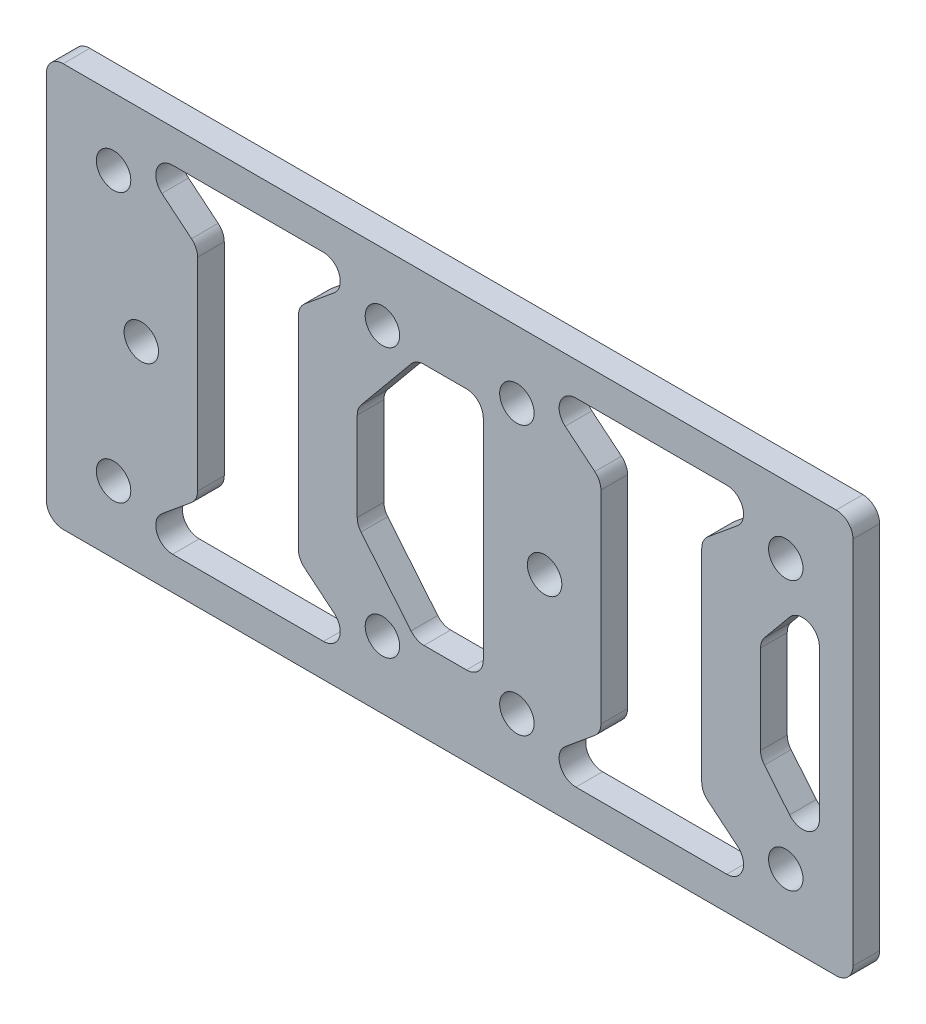
SolidWorks part; units mm, degrees
ref_plane "Front Plane" through (0, 0, 0) normal (0, 0, 1) x (1, 0, 0)
ref_plane "Top Plane" through (0, 0, 0) normal (0, 1, 0) x (1, 0, 0)
ref_plane "Right Plane" through (0, 0, 0) normal (1, 0, 0) x (0, 0, -1)
sketch "Sketch1" plane through (0, 0, 0) normal (0, 0, 1) x (1, 0, 0)
  line L0 (0, 0) -> (50000, 0) construction
  line L1 (48, -24) -> (-48, -24)
  line L2 (48, -24) -> (48, 24)
  line L3 (48, 24) -> (-48, 24)
  line L4 (-48, -24) -> (-48, 24)
  line L5 (48, -24) -> (-24, 12) construction
  line L6 (48, 24) -> (-48, -24) construction
  line L7 (0, 0) -> (0, -50000) construction
  line L8 (-38.5449, 20.05) -> (-30, 13)
  line L9 (-40, 16) -> (-8, 16) construction
  line L10 (-40, 16) -> (-40, -16) construction
  line L11 (-40, -16) -> (-8, -16) construction
  line L12 (-8, 16) -> (-8, -16) construction
  line L13 (-40, 16) -> (-8, -16) construction
  line L14 (-40, -16) -> (-8, 16) construction
  line L16 (-18, 13) -> (-9.4551, 20.05)
  line L17 (-9.4551, 20.05) -> (-38.5449, 20.05)
  line L18 (50, 26) -> (-50, 26) construction
  line L19 (-50, -26) -> (-50, 26) construction
  line L20 (50, -26) -> (-50, -26) construction
  line L21 (50, -26) -> (50, 26) construction
  line L22 (44, 20) -> (-44, 20) construction
  line L23 (-44, -20) -> (-44, 20) construction
  line L24 (44, -20) -> (-44, -20) construction
  line L25 (44, -20) -> (44, 20) construction
  line L26 (-18, -13) -> (-9.4551, -20.05)
  line L28 (-38.5449, -20.05) -> (-30, -13)
  line L29 (-9.4551, -20.05) -> (-38.5449, -20.05)
  line L30 (-44, 14.4843) -> (-44, -14.4843) construction
  line L31 (-44, -14.4843) -> (-37, -6) construction
  line L32 (-37, -6) -> (-37, 6) construction
  line L33 (-37, 6) -> (-44, 14.4843) construction
  line L34 (-24, 0) -> (-24, 50000) construction
  line L35 (-11, -6) -> (-11, 6)
  line L36 (-4, -14.4843) -> (-11, -6)
  line L38 (-11, 6) -> (-4, 14.4843)
  line L42 (11, -6) -> (11, -5.5)
  line L44 (38.5449, -20.05) -> (30, -13)
  line L45 (9.4551, -20.05) -> (38.5449, -20.05)
  line L46 (18, -13) -> (9.4551, -20.05)
  line L47 (37, -6) -> (37, 6)
  line L48 (44, -14.4843) -> (37, -6)
  line L49 (44, 14.4843) -> (44, -14.4843)
  line L50 (37, 6) -> (44, 14.4843)
  line L51 (18, 13) -> (9.4551, 20.05)
  line L53 (38.5449, 20.05) -> (30, 13)
  line L54 (9.4551, 20.05) -> (38.5449, 20.05)
  line L55 (-44, -14.4843) -> (-37, -6) construction
  line L56 (-44, 14.4843) -> (-44, -14.4843) construction
  line L57 (-37, 6) -> (-44, 14.4843) construction
  line L58 (-37, -6) -> (-37, 6) construction
  line L59 (-4, 14.4843) -> (4, 14.4843)
  line L60 (-4, -14.4843) -> (4, -14.4843)
  line L61 (4, 14.4843) -> (4, -14.4843)
  line L62 (18, 13) -> (18, -13)
  line L63 (30, 13) -> (30, -13)
  line L64 (-30, 13) -> (-30, -13)
  line L65 (-18, 13) -> (-18, -13)
  line L66 (-25.7605, 12.8802) -> (-48, 24) construction
  line L67 (11, 5.5) -> (11, 6)
  circle A0 centre (-40, 16) radius 2.05
  circle A1 centre (-8, 16) radius 2.05
  circle A2 centre (-8, -16) radius 2.05
  circle A3 centre (-40, -16) radius 2.05
  circle A4 centre (-24, 0) radius 11 construction
  circle A5 centre (-8, -16) radius 4.05 construction
  circle A6 centre (-40, -16) radius 4.05 construction
  arc A7 (-25.7605, 12.8802) -> (-24, 13) centre (-24, 0) ccw construction
  circle A8 centre (-40, 16) radius 4.05 construction
  circle A9 centre (-8, 16) radius 4.05 construction
  circle A10 centre (-8, -16) radius 0.05 construction
  circle A11 centre (-40, -16) radius 0.05 construction
  circle A12 centre (-24, 0) radius 9 construction
  circle A13 centre (-40, 16) radius 0.05 construction
  circle A14 centre (-8, 16) radius 0.05 construction
  circle A15 centre (8, 16) radius 2.05
  circle A16 centre (8, -16) radius 2.05
  circle A17 centre (40, -16) radius 2.05
  circle A18 centre (24, 0) radius 11 construction
  circle A19 centre (40, 16) radius 2.05
  circle A20 centre (-36.7, 0) radius 2.05
  circle A21 centre (11.3, 0) radius 2.05
  circle A22 centre (-24, 0) radius 13 construction
  point P0 (0, 0)
  point P10 (-24, 0)
  dimension "D5" = 4.1
  dimension "D6" = 22
  dimension "D1" = 96
  dimension "D2" = 48
  dimension "D3" = 32
  dimension "D4" = 8
  dimension "D11" = 12
  dimension "D12" = 12
  dimension "D13" = 48
  dimension "D14" = 11.3
  dimension "D7" = 2
  dimension "D8" = 2
  dimension "D9" = 2
  dimension "D10" = 4
extrude "Boss-Extrude1" add sketch "Sketch1" along normal blind 3.175
fillet "Fillet1" radius 2 30 edges at (38.5449, -20.05, 1.5875) (9.4551, -20.05, 1.5875) (44, -14.4843, 1.5875) (37, -6, 1.5875) (37, 6, 1.5875) (44, 14.4843, 1.5875) (38.5449, 20.05, 1.5875) (9.4551, 20.05, 1.5875) (-48, -24, 1.5875) (-38.5449, -20.05, 1.5875) (-9.4551, -20.05, 1.5875) (-11, -6, 1.5875) (-11, 6, 1.5875) (-9.4551, 20.05, 1.5875) (-38.5449, 20.05, 1.5875) (-48, 24, 1.5875) (48, 24, 1.5875) (48, -24, 1.5875) (-4, -14.4843, 1.5875) (-4, 14.4843, 1.5875) (4, -14.4843, 1.5875) (4, 14.4843, 1.5875) (18, -13, 1.5875) (30, -13, 1.5875) (30, 13, 1.5875) (18, 13, 1.5875) (-30, -13, 1.5875) (-18, -13, 1.5875) (-30, 13, 1.5875) (-18, 13, 1.5875)
